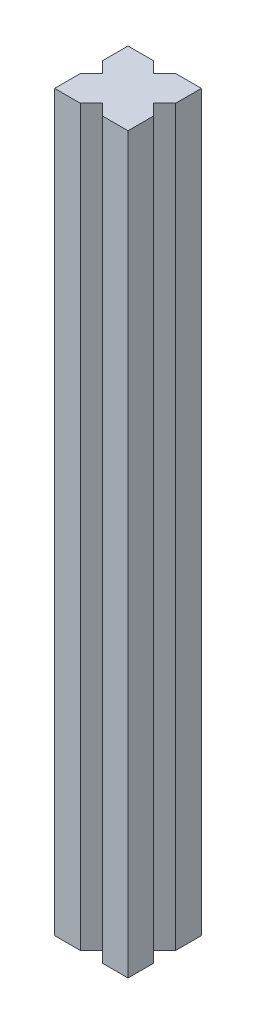
SolidWorks part; units mm, degrees
ref_plane "Front" through (0, 0, 0) normal (0, 0, 1) x (1, 0, 0)
ref_plane "Top" through (0, 0, 0) normal (0, 1, 0) x (1, 0, 0)
ref_plane "Right" through (0, 0, 0) normal (1, 0, 0) x (0, 0, -1)
sketch "Skizze1" plane through (0, 0, 0) normal (0, 1, 0) x (1, 0, 0)
  line L1 (0, 0) -> (20, 0)
  line L2 (0, 0) -> (0, 20)
  line L3 (0, 20) -> (20, 20)
  line L4 (20, 0) -> (20, 20)
  dimension "D1" = 20
extrude "Aufsatz-Linear austragen1" add sketch "Skizze1" along normal blind 200
sketch "Skizze2" plane through (0, 200, 0) normal (0, 1, 0) x (1, 0, 0)
  line L0 (10, 20) -> (10, 0) construction
  line L1 (0, 10) -> (20, 10) construction
  line L2 (7, 20) -> (10, 17)
  line L3 (13, 20) -> (10, 17)
  line L4 (10, 10) -> (20, 20) construction
  line L5 (7, 20) -> (13, 20)
  line L6 (20, 13) -> (17, 10)
  line L7 (20, 7) -> (17, 10)
  line L8 (20, 7) -> (20, 13)
  line L9 (0, 7) -> (0, 13)
  line L10 (0, 7) -> (3, 10)
  line L11 (0, 13) -> (3, 10)
  line L12 (7, 0) -> (13, 0)
  line L13 (13, 0) -> (10, 3)
  line L14 (7, 0) -> (10, 3)
  line L15 (20, 20) -> (0, 20) construction
  line L16 (20, 0) -> (20, 20) construction
  line L17 (0, 0) -> (20, 0) construction
  dimension "D1" = 3
  dimension "D2" = 3
extrude "Schnitt-Linear austragen1" cut sketch "Skizze2" against normal through all
